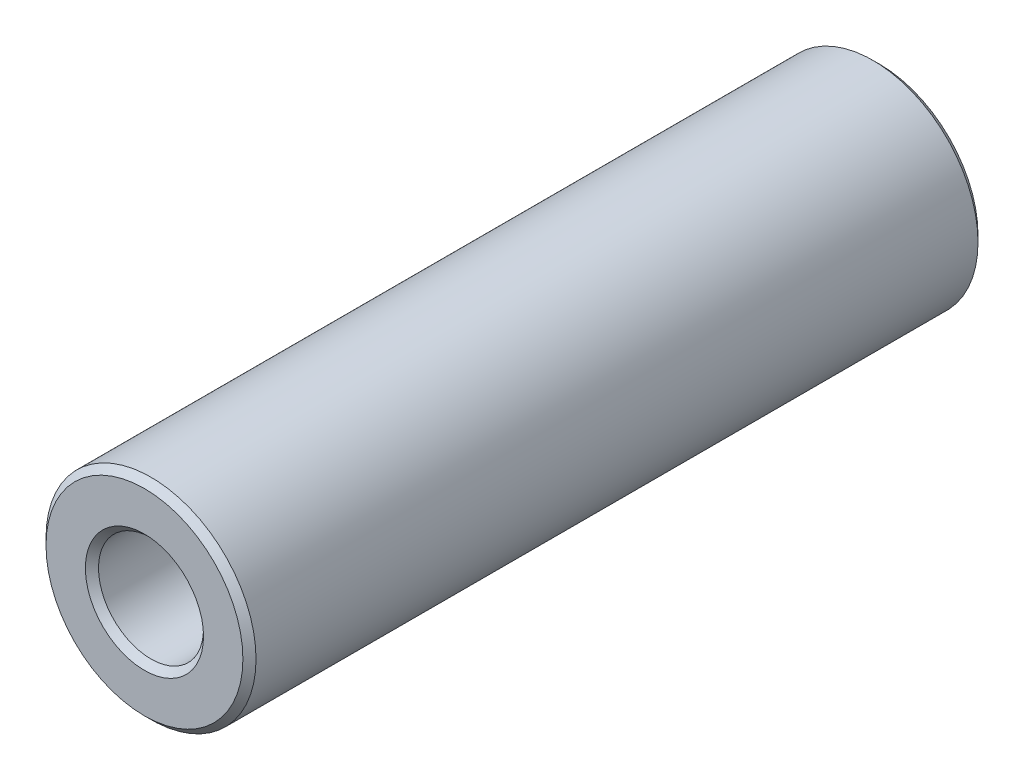
SolidWorks part; units mm, degrees
ref_plane "Plan1" through (0, 0, 0) normal (0, 0, 1) x (1, 0, 0)
ref_plane "Plan2" through (0, 0, 0) normal (0, 1, 0) x (1, 0, 0)
ref_plane "Plan3" through (0, 0, 0) normal (1, 0, 0) x (0, 0, -1)
sketch "Esquisse1" plane through (0, 0, 0) normal (0, 0, 1) x (1, 0, 0)
  circle A0 centre (0, 0) radius 4
  circle A1 centre (0, 0) radius 2
  dimension "D1" = 8
  dimension "D2" = 4
extrude "Base-Extrusion" add sketch "Esquisse1" along normal blind 28
chamfer "Chanfrein1" distance 0.25 angle 45
ref_plane "Plan4" through (0, 0, 14) normal (0, 0, -1) x (-1, 0, 0)
